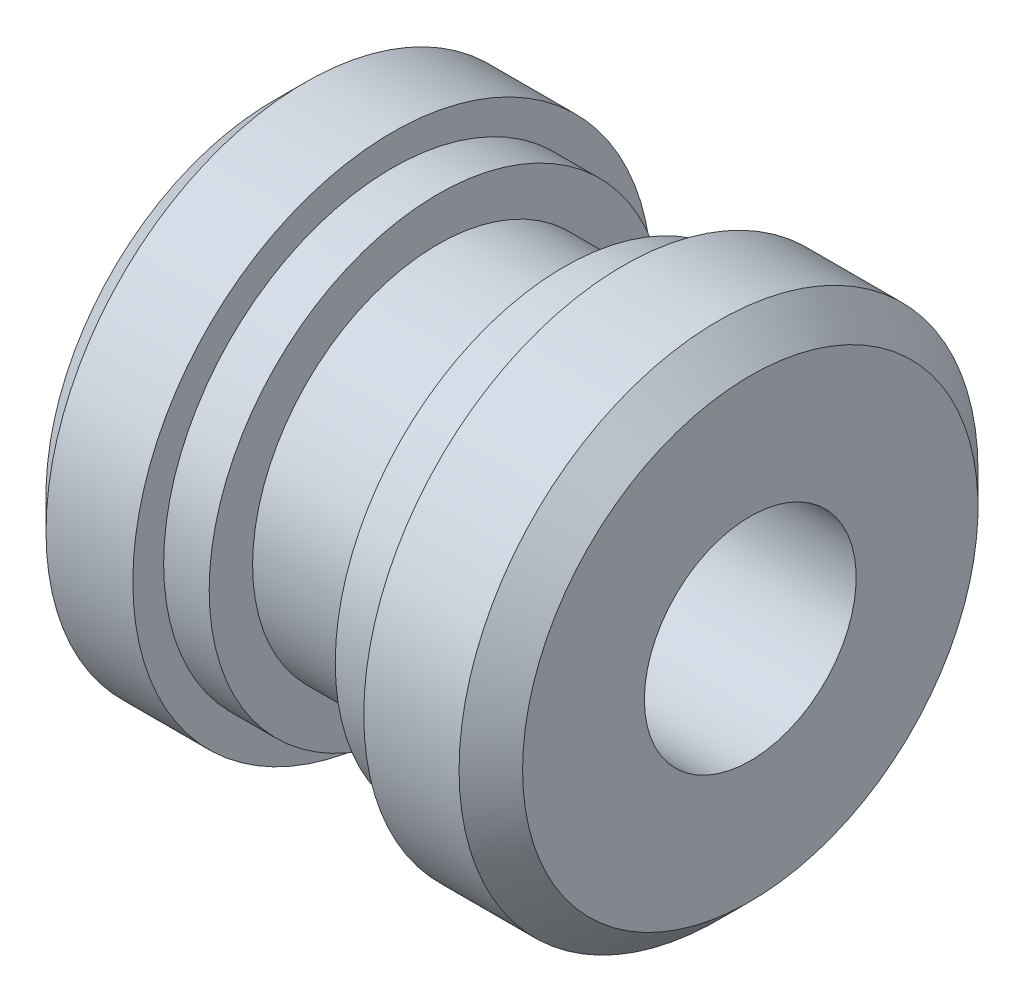
SolidWorks part; units mm, degrees
ref_plane "Front Plane" through (0, 0, 0) normal (0, 0, 1) x (1, 0, 0)
ref_plane "Top Plane" through (0, 0, 0) normal (0, 1, 0) x (1, 0, 0)
ref_plane "Right Plane" through (0, 0, 0) normal (1, 0, 0) x (0, 0, -1)
sketch "Sketch1" plane through (0, 0, 0) normal (0, 0, 1) x (1, 0, 0)
  line L0 (0, 0) -> (45, 0) construction
  line L1 (0, 10) -> (0, 24.5)
  line L2 (0, 24.5) -> (11.1974, 24.5)
  line L3 (11.1974, 24.5) -> (11.1974, 21.5912)
  line L4 (11.1974, 21.5912) -> (15.4983, 21.5912)
  line L5 (15.4983, 21.5912) -> (15.4983, 17.4904)
  line L6 (15.4983, 17.4904) -> (27.4007, 17.4904)
  line L7 (27.4007, 17.4904) -> (27.4007, 21.5912)
  line L8 (27.4007, 21.5912) -> (33.0019, 21.5912)
  line L9 (33.0019, 21.5912) -> (33.0019, 24.5)
  line L10 (33.0019, 24.5) -> (45, 24.5)
  line L11 (45, 24.5) -> (45, 10)
  line L12 (0, 10) -> (45, 10)
  line L13 (22.5, 0) -> (22.5, 32.9686) construction
  dimension "D1" = 45
  dimension "D2" = 49
  dimension "D3" = 20
revolve "Revolve1" add sketch "Sketch1" angle 360 about L0
chamfer "Chamfer1" distance 3 angle 45 1 edges at (45, 0, 24.5)
chamfer "Chamfer2" distance 3 angle 45 1 edges at (0, 0, 24.5)
